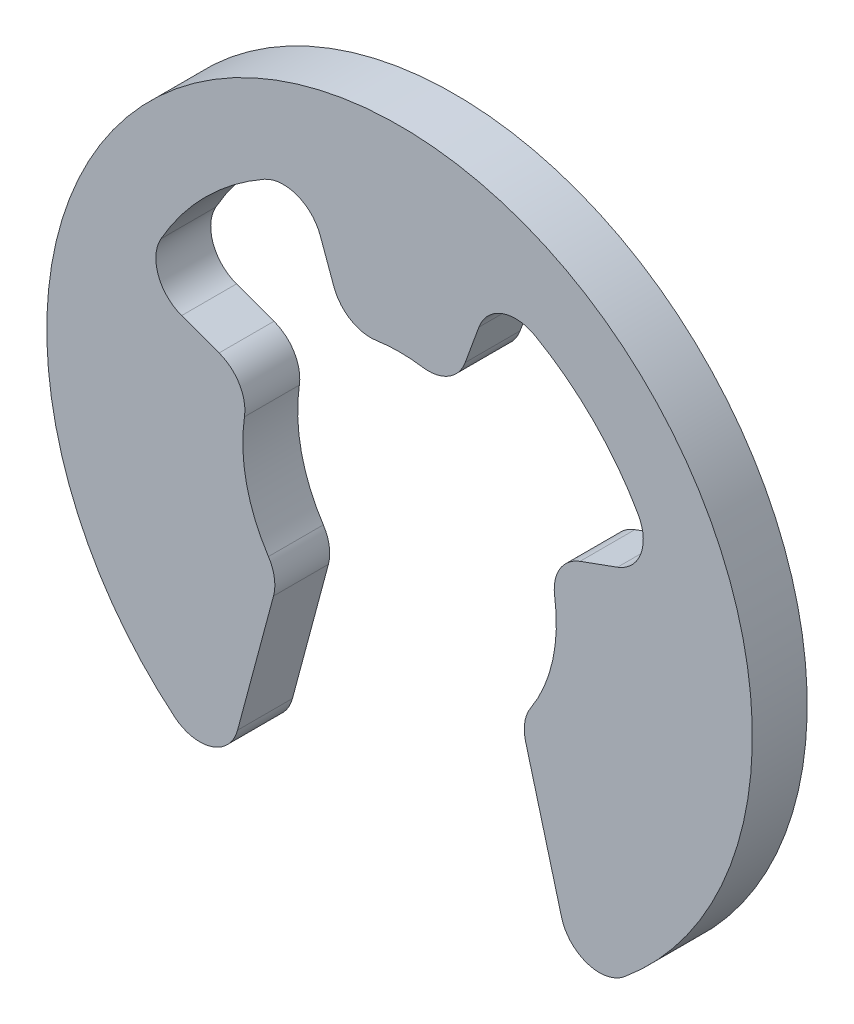
SolidWorks part; units mm, degrees
ref_plane "Plan1" through (0, 0, 0) normal (0, 0, 1) x (1, 0, 0)
ref_plane "Plan2" through (0, 0, 0) normal (0, 1, 0) x (1, 0, 0)
ref_plane "Plan3" through (0, 0, 0) normal (1, 0, 0) x (0, 0, -1)
sketch "Esquisse1" plane through (0, 0, 0) normal (0, 0, 1) x (1, 0, 0)
  line L0 (-1.6077, -1.5002) -> (-2.0664, -3.2118)
  line L1 (0, 0) -> (0, -5.2513) construction
  line L2 (-2.3018, 0.8378) -> (-2.7796, 1.0117)
  line L3 (0, 0) -> (-3.182, 3.182) construction
  line L4 (50, 0) -> (-50, 0) construction
  line L5 (-0.8378, 2.3018) -> (-1.0117, 2.7796)
  line L6 (0.8378, 2.3018) -> (1.0117, 2.7796)
  line L7 (2.3018, 0.8378) -> (2.7796, 1.0117)
  line L8 (1.6077, -1.5002) -> (2.0664, -3.2118)
  arc A0 (2.868, -3.4677) -> (-2.868, -3.4677) centre (0, 0) ccw
  arc A1 (1.6726, -1.0966) -> (1.9782, 0.2943) centre (0, 0) ccw
  arc A2 (-3.0434, 1.7285) -> (-1.7285, 3.0434) centre (0, 0) cw
  arc A3 (3.0434, 1.7285) -> (1.7285, 3.0434) centre (0, 0) ccw
  arc A4 (-1.9782, 0.2943) -> (-1.6726, -1.0966) centre (0, 0) ccw
  arc A5 (0.2943, 1.9782) -> (-0.2943, 1.9782) centre (0, 0) ccw
  arc A6 (-2.0664, -3.2118) -> (-2.868, -3.4677) centre (-2.5493, -3.0824) cw
  arc A7 (-1.6726, -1.0966) -> (-1.6077, -1.5002) centre (-2.0907, -1.3708) cw
  arc A8 (-2.3018, 0.8378) -> (-1.9782, 0.2943) centre (-2.4728, 0.3679) cw
  arc A9 (-3.0434, 1.7285) -> (-2.7796, 1.0117) centre (-2.6086, 1.4816) ccw
  arc A10 (-1.0117, 2.7796) -> (-1.7285, 3.0434) centre (-1.4816, 2.6086) ccw
  arc A11 (-0.2943, 1.9782) -> (-0.8378, 2.3018) centre (-0.3679, 2.4728) cw
  arc A12 (0.8378, 2.3018) -> (0.2943, 1.9782) centre (0.3679, 2.4728) cw
  arc A13 (1.7285, 3.0434) -> (1.0117, 2.7796) centre (1.4816, 2.6086) ccw
  arc A14 (2.7796, 1.0117) -> (3.0434, 1.7285) centre (2.6086, 1.4816) ccw
  arc A15 (1.9782, 0.2943) -> (2.3018, 0.8378) centre (2.4728, 0.3679) cw
  arc A16 (1.6077, -1.5002) -> (1.6726, -1.0966) centre (2.0907, -1.3708) cw
  arc A17 (2.868, -3.4677) -> (2.0664, -3.2118) centre (2.5493, -3.0824) cw
  point P19 (0, 4.5)
  point P22 (-2.25, -3.8971)
  point P27 (-1.8794, 0.684)
  point P30 (-3.2889, 1.1971)
  point P33 (-1.1971, 3.2889)
  point P38 (0.684, 1.8794)
  point P41 (1.1971, 3.2889)
  point P44 (3.2889, 1.1971)
  point P51 (2.25, -3.8971)
  dimension "D1" = 9
  dimension "D2" = 4
  dimension "D4" = 3.5
  dimension "D7" = 0.5
  dimension "D3" = 15
  dimension "D5" = 25
  dimension "D6" = 45
extrude "Base-Extrusion" add sketch "Esquisse1" along normal blind 0.7
